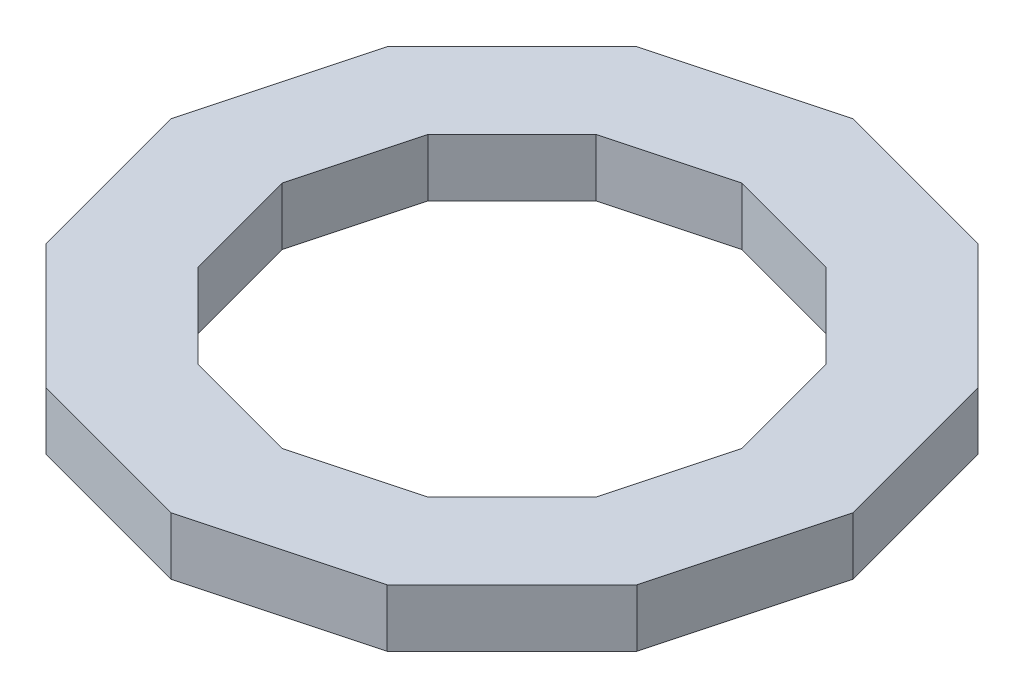
SolidWorks part; units mm, degrees
ref_plane "Front Plane" through (0, 0, 0) normal (0, 0, 1) x (1, 0, 0)
ref_plane "Top Plane" through (0, 0, 0) normal (0, 1, 0) x (1, 0, 0)
ref_plane "Right Plane" through (0, 0, 0) normal (1, 0, 0) x (0, 0, -1)
sketch "Sketch1" plane through (0, 0, 0) normal (0, 1, 0) x (1, 0, 0)
  line L0 (0, 0) -> (76.0444, 0) construction
  line L1 (76.0444, 0) -> (65.8563, 38.0222)
  line L2 (65.8563, 38.0222) -> (38.0222, 65.8563)
  line L3 (38.0222, 65.8563) -> (0, 76.0444)
  line L4 (0, 76.0444) -> (-38.0222, 65.8563)
  line L5 (-38.0222, 65.8563) -> (-65.8563, 38.0222)
  line L6 (-65.8563, 38.0222) -> (-76.0444, 0)
  line L7 (-76.0444, 0) -> (-65.8563, -38.0222)
  line L8 (-65.8563, -38.0222) -> (-38.0222, -65.8563)
  line L9 (-38.0222, -65.8563) -> (0, -76.0444)
  line L10 (0, -76.0444) -> (38.0222, -65.8563)
  line L11 (38.0222, -65.8563) -> (65.8563, -38.0222)
  line L12 (65.8563, -38.0222) -> (76.0444, 0)
  line L13 (112.8588, 0) -> (97.7386, 56.4294)
  line L14 (97.7386, 56.4294) -> (56.4294, 97.7386)
  line L15 (56.4294, 97.7386) -> (0, 112.8588)
  line L16 (0, 112.8588) -> (-56.4294, 97.7386)
  line L17 (-56.4294, 97.7386) -> (-97.7386, 56.4294)
  line L18 (-97.7386, 56.4294) -> (-112.8588, 0)
  line L19 (-112.8588, 0) -> (-97.7386, -56.4294)
  line L20 (-97.7386, -56.4294) -> (-56.4294, -97.7386)
  line L21 (-56.4294, -97.7386) -> (0, -112.8588)
  line L22 (0, -112.8588) -> (56.4294, -97.7386)
  line L23 (56.4294, -97.7386) -> (97.7386, -56.4294)
  line L24 (97.7386, -56.4294) -> (112.8588, 0)
  circle A0 centre (0, 0) radius 73.4532 construction
  circle A1 centre (0, 0) radius 109.0132 construction
  dimension "D1" = 35.56
  dimension "D2" = 58.42
extrude "Boss-Extrude1" add sketch "Sketch1" along normal blind 19.05
